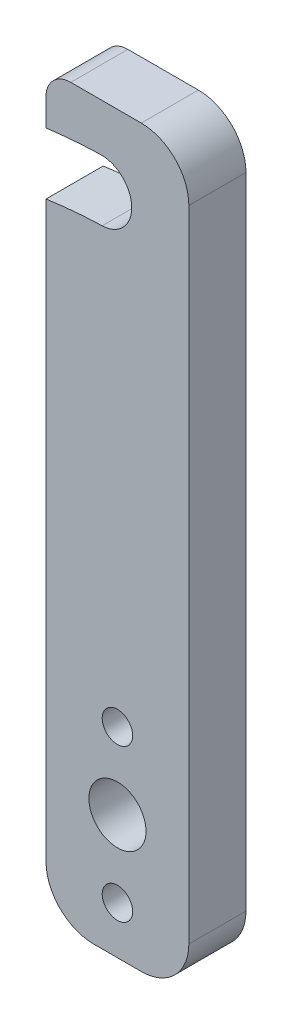
SolidWorks part; units mm, degrees
material "MDF"
ref_plane "Plano frontal" through (0, 0, 0) normal (0, 0, 1) x (1, 0, 0)
ref_plane "Plano superior" through (0, 0, 0) normal (0, 1, 0) x (1, 0, 0)
ref_plane "Plano direito" through (0, 0, 0) normal (1, 0, 0) x (0, 0, -1)
sketch "Esboço1" plane through (0, 0, 0) normal (0, 0, 1) x (1, 0, 0)
  line L0 (0, -17.5864) -> (0, -33.5864) construction
  line L1 (-7.5, -38.5864) -> (7.5, -38.5864)
  line L2 (-7.5, -38.5864) -> (-7.5, 38.5864)
  line L3 (-7.5, 38.5864) -> (7.5, 38.5864)
  line L4 (7.5, -38.5864) -> (7.5, 38.5864)
  line L5 (-7.5, -38.5864) -> (7.5, 38.5864) construction
  line L6 (-7.5, 38.5864) -> (7.5, -38.5864) construction
  circle A0 centre (0, -33.5864) radius 1.6
  circle A1 centre (0, -17.5864) radius 1.6
  arc A3 (-1.6985, 30.3879) -> (-7.9545, 29.8458) centre (0, -25.5864) ccw construction
  arc A4 (-1.7956, 33.5864) -> (-8.4091, 33.0133) centre (0, -25.5864) ccw
  arc A5 (-1.6015, 27.1893) -> (-7.5, 26.6782) centre (0, -25.5864) ccw
  arc A6 (-1.6015, 27.1893) -> (-1.7956, 33.5864) centre (-1.6985, 30.3879) ccw
  arc A7 (-8.4091, 33.0133) -> (-7.5, 26.6782) centre (-7.9545, 29.8458) ccw
  circle A8 centre (0, -25.5864) radius 3
  point P0 (0, 0)
  point P14 (-4.8341, 30.2046)
  point P20 (1.5, 30.4849)
  point P22 (0, 0)
  dimension "D1" = 56
  dimension "D2" = 3.2
  dimension "D4" = 16
  dimension "D6" = 3.2
  dimension "D8" = 6
  dimension "D3" = 15
  dimension "D5" = 5
  dimension "D7" = 5
  dimension "D9" = 6
extrude "Ressalto-extrusão1" add sketch "Esboço1" along normal blind 6
fillet "Filete1" radius 5 3 edges at (-7.5, -38.5864, 3) (7.5, -38.5864, 3) (7.5, 38.5864, 3)
fillet "Filete2" radius 2.6 1 edges at (-7.5, 38.5864, 3)
